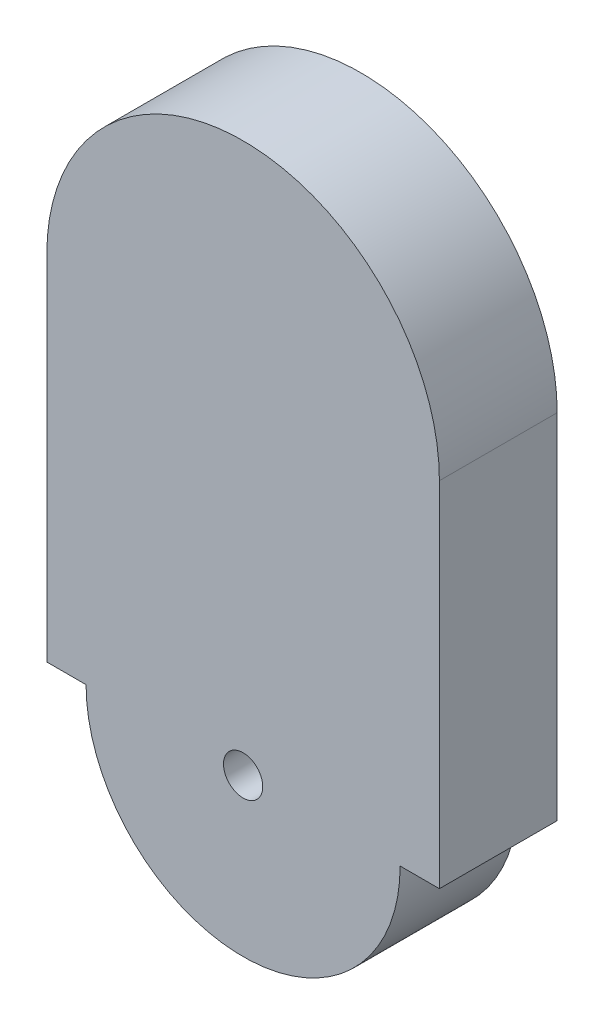
SolidWorks part; units mm, degrees
ref_plane "Front" through (0, 0, 0) normal (0, 0, 1) x (1, 0, 0)
ref_plane "Top" through (0, 0, 0) normal (0, 1, 0) x (1, 0, 0)
ref_plane "Right" through (0, 0, 0) normal (1, 0, 0) x (0, 0, -1)
sketch "Sketch2" plane through (0, 0, 0) normal (0, 0, 1) x (1, 0, 0)
  line L0 (0, 28.575) -> (0, -28.575) construction
  line L1 (0, -50) -> (0, 50) construction
  line L2 (31.75, 28.575) -> (31.75, -28.575)
  line L3 (-31.75, 28.575) -> (-31.75, -28.575)
  line L4 (-31.75, -28.575) -> (-25.4, -28.575)
  line L5 (0, -7.1144) -> (0, -28.575) construction
  line L8 (25.4, -28.575) -> (31.75, -28.575)
  line L9 (50, 0) -> (-50, 0) construction
  arc A0 (31.75, 28.575) -> (-31.75, 28.575) centre (0, 28.575) ccw
  arc A3 (-25.4, -28.575) -> (25.4, -28.575) centre (0, -28.575) ccw
  point P5 (0, 60.325)
  point P11 (0, -53.975)
  point P12 (31.75, 0)
  point P17 (0, 0)
  point P18 (31.75, 28.575)
  point P20 (0, 0)
  point P21 (-55.8279, -29.725)
  point P23 (0, 0)
  dimension "D2" = 31.75
  dimension "D4" = 25.4
  dimension "D1" = 63.5
  dimension "D3" = 114.3
extrude "Boss-Extrude1" add sketch "Sketch2" along normal blind 19.05
sketch "Sketch3" plane through (0, 0, 0) normal (0, 0, -1) x (-1, 0, 0)
  point P0 (0, -28.575)
hole_wizard "1/4 (0.25) Diameter Hole1" positions "Sketch4" profile "Sketch5" hole size "1/4" standard "ANSI Inch" end condition through all
sketch "Sketch4" plane through (0, 0, 0) normal (0, 0, -1) x (-1, 0, 0)
  point P0 (0, -28.575)
sketch "Sketch5" plane through (0, -28.575, 0) normal (1, 0, 0) x (0, 1, 0)
  line L0 (0, 0) -> (0, 19.05)
  line L1 (0, 19.05) -> (3.175, 19.05)
  line L2 (3.175, 19.05) -> (3.175, 0)
  line L5 (3.175, 0) -> (0, 0)
  line L11 (0, -6.35) -> (0, 107.95) construction
  dimension "Thru Hole Dia." = 6.35
  dimension "Thru Hole Depth" = 19.05
